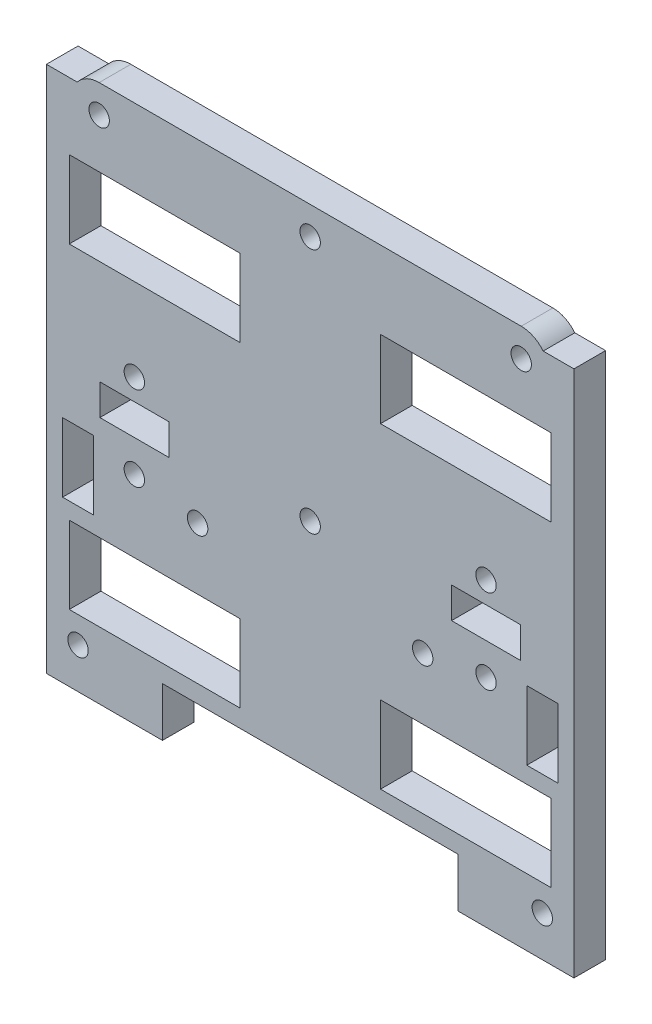
SolidWorks part; units mm, degrees
ref_plane "Front Plane" through (0, 0, 0) normal (0, 0, 1) x (1, 0, 0)
ref_plane "Top Plane" through (0, 0, 0) normal (0, 1, 0) x (1, 0, 0)
ref_plane "Right Plane" through (0, 0, 0) normal (1, 0, 0) x (0, 0, -1)
sketch "Sketch1" plane through (0, 0, 0) normal (0, 0, 1) x (1, 0, 0)
  line L0 (0, -37.5) -> (0, 37.5) construction
  line L1 (-47.5, -37.5) -> (47.5, -37.5)
  line L2 (-47.5, -37.5) -> (-47.5, 37.5)
  line L3 (-47.5, 37.5) -> (47.5, 37.5)
  line L4 (47.5, -37.5) -> (47.5, 37.5)
  line L5 (-47.5, -37.5) -> (47.5, 37.5) construction
  line L6 (-47.5, 37.5) -> (47.5, -37.5) construction
  line L7 (-47.5, 0) -> (47.5, 0) construction
  line L8 (-47.5, 22.5) -> (47.5, 22.5) construction
  line L9 (34.25, 17) -> (10, 28) construction
  line L10 (-34.25, 28) -> (-10, 28)
  line L11 (-34.25, 28) -> (-34.25, 17)
  line L12 (-34.25, 17) -> (-10, 17)
  line L13 (-10, 28) -> (-10, 17)
  line L14 (-34.25, 28) -> (-10, 17) construction
  line L15 (-34.25, 17) -> (-10, 28) construction
  line L16 (34.25, 28) -> (10, 17) construction
  line L17 (10, 28) -> (10, 17)
  line L18 (34.25, 17) -> (10, 17)
  line L19 (34.25, 28) -> (34.25, 17)
  line L20 (34.25, 28) -> (10, 28)
  line L21 (34.25, -28) -> (10, -17) construction
  line L22 (-34.25, -17) -> (-10, -28) construction
  line L23 (-34.25, -28) -> (-10, -17) construction
  line L24 (34.25, -17) -> (10, -28) construction
  line L25 (34.25, -28) -> (10, -28)
  line L26 (34.25, -28) -> (34.25, -17)
  line L27 (34.25, -17) -> (10, -17)
  line L28 (10, -28) -> (10, -17)
  line L29 (-10, -28) -> (-10, -17)
  line L30 (-34.25, -17) -> (-10, -17)
  line L31 (-34.25, -28) -> (-34.25, -17)
  line L32 (-34.25, -28) -> (-10, -28)
  point P0 (0, 0)
  point P12 (-22.125, 22.5)
  point P21 (22.125, 22.5)
  point P30 (22.125, -22.5)
  point P31 (-22.125, -22.5)
  dimension "D1" = 95
  dimension "D2" = 75
  dimension "D3" = 22.5
  dimension "D4" = 24.25
  dimension "D5" = 11
  dimension "D6" = 10
extrude "Boss-Extrude1" add sketch "Sketch1" along normal blind 4.5
sketch "Sketch8" plane through (0, 0, 4.5) normal (0, 0, 1) x (1, 0, 0)
  line L0 (-47.5, 37.5) -> (-47.5, -37.5) construction
  line L1 (47.5, -37.5) -> (47.5, 37.5) construction
  circle A0 centre (-47.5, 29.5) radius 8
  circle A1 centre (47.5, 29.5) radius 8
  dimension "D1" = 16
extrude "Boss-Extrude2" [suppressed] add sketch "Sketch8" against normal through all
sketch "Sketch2" plane through (0, 0, 4.5) normal (0, 0, 1) x (1, 0, 0)
  line L0 (0, -37.5) -> (0, 37.5) construction
  line L1 (-47.5, -37.5) -> (47.5, -37.5) construction
  line L2 (47.5, 37.5) -> (-47.5, 37.5) construction
  line L3 (-47.5, 0) -> (47.5, 0) construction
  line L4 (-47.5, 37.5) -> (-47.5, -37.5) construction
  line L5 (47.5, -37.5) -> (47.5, 37.5) construction
  line L6 (-40, 0) -> (40, 0) construction
  line L7 (-30, 35) -> (30, 35) construction
  circle A0 centre (-30, 35) radius 1.45
  circle A1 centre (30, 35) radius 1.45
  circle A2 centre (40, 0) radius 1.45
  circle A3 centre (-40, 0) radius 1.45
  circle A4 centre (0, 35) radius 1.45
  dimension "D1" = 2.9
  dimension "D7" = 2.9
  dimension "D8" = 2.9
  dimension "D9" = 2.9
  dimension "D2" = 30
  dimension "D3" = 35
  dimension "D4" = 80
  dimension "D5" = 40
  dimension "D6" = 0
extrude "screwHoles" cut sketch "Sketch2" against normal through all
sketch "Sketch3" plane through (0, 0, 4.5) normal (0, 0, 1) x (1, 0, 0)
  line L0 (-47.5, -20) -> (26.0486, -20) construction
  line L1 (-47.5, 37.5) -> (-47.5, -37.5) construction
  line L3 (0, 37.5) -> (0, -37.5) construction
  line L4 (47.5, 37.5) -> (-47.5, 37.5) construction
  line L5 (-47.5, -37.5) -> (47.5, -37.5) construction
  line L6 (18.95, -22.2) -> (9.05, -17.8) construction
  line L7 (-18.95, -17.8) -> (-9.05, -17.8)
  line L8 (-18.95, -17.8) -> (-18.95, -22.2)
  line L9 (-18.95, -22.2) -> (-9.05, -22.2)
  line L10 (-9.05, -17.8) -> (-9.05, -22.2)
  line L11 (-18.95, -17.8) -> (-9.05, -22.2) construction
  line L12 (-18.95, -22.2) -> (-9.05, -17.8) construction
  line L13 (18.95, -17.8) -> (9.05, -22.2) construction
  line L14 (9.05, -17.8) -> (9.05, -22.2)
  line L15 (18.95, -22.2) -> (9.05, -22.2)
  line L16 (18.95, -17.8) -> (18.95, -22.2)
  line L17 (18.95, -17.8) -> (9.05, -17.8)
  line L18 (-47.5, 37.5) -> (-47.5, -37.5) construction
  point P2 (-47.5, 0)
  point P12 (-14, -20)
  point P21 (14, -20)
  dimension "D1" = 9.9
  dimension "D2" = 4.4
  dimension "D3" = 14
  dimension "D4" = 20
extrude "BeltClamp" [suppressed] cut sketch "Sketch3" against normal through all
sketch "Sketch4" plane through (0, 0, 4.5) normal (0, 0, 1) x (1, 0, 0)
  line L0 (-47.5, 0) -> (47.5, 0) construction
  line L1 (-47.5, 37.5) -> (-47.5, -37.5) construction
  line L2 (47.5, -37.5) -> (47.5, 37.5) construction
  line L3 (0, 0) -> (0, 33.55) construction
  line L4 (-29.9, 2.2) -> (-20.1, 2.2)
  line L5 (-29.9, 2.2) -> (-29.9, -2.2)
  line L6 (-29.9, -2.2) -> (-20.1, -2.2)
  line L7 (-20.1, 2.2) -> (-20.1, -2.2)
  line L8 (-29.9, 2.2) -> (-20.1, -2.2) construction
  line L9 (-29.9, -2.2) -> (-20.1, 2.2) construction
  line L10 (29.9, -2.2) -> (20.1, 2.2) construction
  line L11 (29.9, 2.2) -> (20.1, -2.2) construction
  line L12 (20.1, 2.2) -> (20.1, -2.2)
  line L13 (29.9, -2.2) -> (20.1, -2.2)
  line L14 (29.9, 2.2) -> (29.9, -2.2)
  line L15 (29.9, 2.2) -> (20.1, 2.2)
  line L16 (-29.9, -2.2) -> (-20.1, 2.2) construction
  circle A0 centre (-40, 0) radius 1.45 construction
  circle A1 centre (0, 35) radius 1.45 construction
  circle A2 centre (0, 0) radius 1.45
  point P6 (-25, 0)
  point P22 (25, 0)
  dimension "D2" = 4.4
  dimension "D5" = 2.9
  dimension "D3" = 0
  dimension "D1" = 9.8
  dimension "D4" = 25
extrude "Cut-Extrude3" cut sketch "Sketch4" against normal through all
sketch "Sketch5" plane through (0, 0, 4.5) normal (0, 0, 1) x (1, 0, 0)
  line L0 (-47.5, -9.75) -> (47.5, -9.75) construction
  line L1 (-47.5, 37.5) -> (-47.5, -37.5) construction
  line L2 (47.5, -37.5) -> (47.5, 37.5) construction
  line L4 (0, -37.5) -> (0, 37.5) construction
  line L5 (-47.5, -37.5) -> (47.5, -37.5) construction
  line L6 (47.5, 37.5) -> (-47.5, 37.5) construction
  line L7 (-30.8, -14.65) -> (-35.2, -4.85) construction
  line L8 (30.8, -4.85) -> (35.2, -4.85)
  line L9 (30.8, -4.85) -> (30.8, -14.65)
  line L10 (30.8, -14.65) -> (35.2, -14.65)
  line L11 (35.2, -4.85) -> (35.2, -14.65)
  line L12 (30.8, -4.85) -> (35.2, -14.65) construction
  line L13 (30.8, -14.65) -> (35.2, -4.85) construction
  line L14 (-30.8, -4.85) -> (-35.2, -14.65) construction
  line L15 (-35.2, -4.85) -> (-35.2, -14.65)
  line L16 (-30.8, -14.65) -> (-35.2, -14.65)
  line L17 (-30.8, -4.85) -> (-30.8, -14.65)
  line L18 (-30.8, -4.85) -> (-35.2, -4.85)
  line L19 (33, -9.75) -> (33, -37.5) construction
  line L20 (-33, -9.75) -> (-33, -37.5) construction
  line L21 (-33, -31.75) -> (33, -31.75) construction
  circle A0 centre (33, -31.75) radius 1.45
  circle A1 centre (-33, -31.75) radius 1.45
  point P15 (33, -9.75)
  point P24 (-33, -9.75)
  dimension "D5" = 2.9
  dimension "D2" = 9.8
  dimension "D3" = 4.4
  dimension "D4" = 33
  dimension "D6" = 22
  dimension "D1" = 9.75
extrude "Cut-Extrude4" cut sketch "Sketch5" against normal through all
sketch "Sketch9" plane through (0, 0, 4.5) normal (0, 0, 1) x (1, 0, 0)
  line L0 (47.5, 37.5) -> (-47.5, 37.5) construction
  line L1 (0, 37.5) -> (0, -37.5) construction
  line L2 (-47.5, -37.5) -> (47.5, -37.5) construction
  line L3 (50.5, 35) -> (45.5, 35) construction
  line L4 (-50.5, 35) -> (-45.5, 35) construction
  circle A0 centre (-30, 35) radius 4
  circle A1 centre (-30, 35) radius 1.45
  circle A2 centre (-30, 35) radius 1.45 construction
  circle A3 centre (30, 35) radius 1.45
  circle A4 centre (30, 35) radius 4
  point P17 (0, -37.5)
  dimension "D1" = 8
extrude "Boss-Extrude3" add sketch "Sketch9" against normal through all
sketch "Sketch10" plane through (0, 0, 4.5) normal (0, 0, 1) x (1, 0, 0)
  line L0 (-60, 37.5) -> (-37.5, 37.5)
  line L1 (-37.5, 37.5) -> (-37.5, -37.5)
  line L2 (-47.5, -37.5) -> (47.5, -37.5) construction
  line L3 (-37.5, -37.5) -> (-60, -37.5)
  line L4 (-60, -37.5) -> (-60, 37.5)
  line L5 (0, 37.5) -> (0, -37.5) construction
  line L6 (26.8775, 37.5) -> (-26.8775, 37.5) construction
  line L7 (60, -37.5) -> (60, 37.5)
  line L8 (37.5, -37.5) -> (60, -37.5)
  line L9 (37.5, 37.5) -> (37.5, -37.5)
  line L10 (60, 37.5) -> (37.5, 37.5)
  line L11 (-60, -37.5) -> (-60, 37.5)
  line L12 (-33.1225, 37.5) -> (-47.5, 37.5) construction
  line M3 (47.5, -37.5) -> (47.5, 37.5)
  line M7 (-47.5, 37.5) -> (-47.5, -37.5)
  line M8 (-47.5, -37.5) -> (47.5, -37.5)
  dimension "D3" = 0
  dimension "D1" = 75
  dimension "D2" = 60
extrude "Cut-Extrude5" cut sketch "Sketch10" against normal through all contours L1 L0 M7 M8 | L10 L9 M3 M8
sketch "Sketch11" plane through (0, 0, 4.5) normal (0, 0, 1) x (1, 0, 0)
  line L0 (-30, 39) -> (30, 39)
  line L1 (30, 39) -> (26.8775, 37.5)
  line L2 (26.8775, 37.5) -> (-26.8775, 37.5)
  line L3 (-26.8775, 37.5) -> (-30, 39)
  arc A0 (-26.8775, 37.5) -> (-33.1225, 37.5) centre (-30, 35) ccw construction
  arc A1 (33.1225, 37.5) -> (26.8775, 37.5) centre (30, 35) ccw construction
extrude "Boss-Extrude4" add sketch "Sketch11" against normal through all
sketch "Sketch12" plane through (0, 0, 4.5) normal (0, 0, 1) x (1, 0, 0)
  line L0 (-37.5, -8.25) -> (37.5, -8.25) construction
  line L1 (-37.5, 37.5) -> (-37.5, -37.5) construction
  line L2 (37.5, 37.5) -> (37.5, -37.5) construction
  line L3 (0, 0) -> (0, -37.5) construction
  line L4 (-37.5, -37.5) -> (37.5, -37.5) construction
  circle A0 centre (-16, -8.25) radius 1.45
  circle A1 centre (16, -8.25) radius 1.45
  dimension "D2" = 2.9
  dimension "D1" = 16
  dimension "D3" = 8.25
extrude "FanBraceScrews" cut sketch "Sketch12" against normal through all
sketch "Sketch13" plane through (0, 0, 4.5) normal (0, 0, 1) x (1, 0, 0)
  line L0 (-37.5, -37.5) -> (37.5, -37.5) construction
  line L1 (-21, -44.5) -> (21, -44.5)
  line L2 (-21, -44.5) -> (-21, -30.5)
  line L3 (-21, -30.5) -> (21, -30.5)
  line L4 (21, -44.5) -> (21, -30.5)
  line L5 (-21, -44.5) -> (21, -30.5) construction
  line L6 (-21, -30.5) -> (21, -44.5) construction
  point P0 (0, -37.5)
  dimension "D1" = 42
  dimension "D2" = 7
extrude "Cut-Extrude7" cut sketch "Sketch13" against normal through all
sketch "Sketch14" plane through (0, 0, 4.5) normal (0, 0, 1) x (1, 0, 0)
  line L0 (16, -9.7) -> (16, 3.75) construction
  line L1 (0, 0) -> (0, -40.3958) construction
  line L2 (-16, -9.7) -> (-16, 3.75) construction
  circle A0 centre (16, -8.25) radius 1.45 construction
  circle A1 centre (16, 3.75) radius 1.45
  circle A2 centre (-16, 3.75) radius 1.45
  dimension "D2" = 2.9
  dimension "D1" = 12
extrude "Cut-Extrude8" [suppressed] cut sketch "Sketch14" against normal through all
sketch "Sketch15" plane through (0, 0, 4.5) normal (0, 0, 1) x (1, 0, 0)
  line L0 (-25, 5.25) -> (-25, -6.75) construction
  line L2 (0, 0) -> (0, -11.0705) construction
  line L3 (16, -8.3509) -> (25, -6.75) construction
  line L4 (25, 5.25) -> (25, -6.75) construction
  circle A0 centre (-25, 5.25) radius 1.45
  circle A1 centre (-25, -6.75) radius 1.45
  circle A2 centre (25, -6.75) radius 1.45
  circle A3 centre (25, 5.25) radius 1.45
  circle A5 centre (-16, -8.25) radius 1.45 construction
  dimension "D1" = 12
  dimension "D3" = 2.9
  dimension "D4" = 2.9
  dimension "D2" = 25
  dimension "D5" = 1.5
extrude "BeltClipScrews" cut sketch "Sketch15" against normal through all
sketch "Sketch16" [suppressed] plane through (0, 0, 4.5) normal (0, 0, 1) x (1, 0, 0)
  line L0 (0, 0) -> (0, -11.3016) construction
  line L1 (-30.1, 2.35) -> (-19.9, 2.35)
  line L2 (-30.1, 2.35) -> (-30.1, -2.35)
  line L3 (-30.1, -2.35) -> (-19.9, -2.35)
  line L4 (-19.9, 2.35) -> (-19.9, -2.35)
  line L5 (-35.35, -4.65) -> (-30.65, -4.65)
  line L6 (-35.35, -4.65) -> (-35.35, -14.85)
  line L7 (-35.35, -14.85) -> (-30.65, -14.85)
  line L8 (-30.65, -4.65) -> (-30.65, -14.85)
  line L9 (30.65, -4.65) -> (30.65, -14.85)
  line L10 (35.35, -14.85) -> (30.65, -14.85)
  line L11 (35.35, -4.65) -> (35.35, -14.85)
  line L12 (35.35, -4.65) -> (30.65, -4.65)
  line L13 (19.9, 2.35) -> (19.9, -2.35)
  line L14 (30.1, -2.35) -> (19.9, -2.35)
  line L15 (30.1, 2.35) -> (30.1, -2.35)
  line L16 (30.1, 2.35) -> (19.9, 2.35)
  line L17 (-30.65, -4.65) -> (-30.65, -14.85)
extrude "Boss-Extrude5" [suppressed] add sketch "Sketch16" against normal through all contours L8 L5 L6 L7 | L4 L1 L2 L3 | L15 L16 L13 L14 | L11 L12 L9 L10
equation "\"X-ROD-SPACING\"=45"
equation "\"Y-ROD-SPACING\"=75"
equation "\"Z-ROD-SPACING\"=17.5"
equation "\"Y-BED-OFFSET\"=2"
equation "\"Y-BED-ROD-INSET\"=3.5"
equation "\"Y-BED-SCREW-SPACING\"=209"
equation "\"Y-BED-SCREW-CUTOUT-SLOT-HEIGHT\"=2"
equation "\"T-SLOT-NUT-FILLET-RADIUS\"=0.5"
equation "\"T-SLOT-SCREW-SHAFT-RADIUS\"=1.55"
equation "\"T-SLOT-SCREW-SHAFT-CUTOUT-LENGTH\"=11.0"
equation "\"T-SLOT-NUT-DEPTH\"=3.5"
equation "\"T-SLOT-NUT-WIDTH\"=2.85"
equation "\"T-SLOT-NUT-END-DISTANCE\"=8"
equation "\"ACRYLIC-THICKNESS\"=10"
equation "\"ACRYLIC-THICKNESS2\"=4.5"
equation "\"ACRYLIC-TAB-CUTOUT-SIZE\"=\"ACRYLIC-THICKNESS\"+\"ACRYLIC-TAB-TOLERANCE\"*2"
equation "\"ACRYLIC-TAB-WIDTH\"=\"ACRYLIC-THICKNESS\""
equation "\"ACRYLIC-M3-HOLE\"=2.9"
equation "\"SMOOTHROD-CAP-SCREW-DISTANCE\"=20"
equation "\"FRAME-WIDTH-INNER\"=370"
equation "\"NEMA17-HOLE-SPACING\"=31"
equation "\"NEMA17-CENTRAL-CUTOUT\"=22.5"
equation "\"Z-BRACKET-REACH\"=55"
equation "\"Z-ROD-INSET\"=16"
equation "\"TOP-BRACKET-SPACING\"=40"
equation "\"SMOOTHROD-X-LENGTH\"=350"
equation "\"SMOOTHROD-Y-LENGTH\"=350"
equation "\"SMOOTHROD-Z-LENGTH\"=350"
equation "\"SMOOTHROD-TIGHTENING-HEADROOM\"=.25"
equation "\"LEADSCREW-Z-LENGTH\"=300"
equation "\"SCREW-LENGTH-FRAME\"=\"ACRYLIC-THICKNESS\" + 10"
equation "\"SCREW-LENGTH-MOTOR\"=\"ACRYLIC-THICKNESS\" + 5"
equation "\"SCREW-HEAD-RADIUS\"=6"
equation "\"PRINTED-X-SMOOTHROD-DIAMETER\"=9.4"
equation "\"PRINTED-X-SMOOTHROD-CUTOUT\"=10"
equation "\"PRINTED-X-BASE-HEIGHT\"=10"
equation "\"PRINTED-LM8UU-CUTOUT-SIZE\"=15.5"
equation "\"PRINTED-LM8UU-CUTOUT-LENGTH\"=24.5"
equation "\"PRINTED-X-IDLER-HEIGHT\"=16"
equation "\"PSU-MOUNTING-WIDTH\"=95"
equation "\"PSU-MOUNTING-HEIGHT\"=177"
equation "\"Y-BELT-TO-ROD-DISTANCE\"=20"
equation "\"SPOOL-HOLDER-ROD-SPACING\"=150"
equation "\"D3@Sketch1\"=\"X-ROD-SPACING\"/2"
equation "\"D4@Sketch1\"=\"ACRYLIC-X-CARRIAGE-LM8UU-CUTOUT-WIDTH\""
equation "\"D1@Boss-Extrude1\"=\"ACRYLIC-THICKNESS2\""
equation "\"D1@Sketch2\"=\"ACRYLIC-M3-HOLE\""
equation "\"D1@Sketch3\"=\"ACRYLIC-TAB-CUTOUT-SIZE\""
equation "\"D2@Sketch3\"=\"ACRYLIC-THICKNESS2\"+\"ACRYLIC-TAB-TOLERANCE\"*2"
equation "\"ACRYLIC-X-CARRIAGE-WIDTH\"=55"
equation "\"ACRYLIC-X-CARRIAGE-HEIGHT\"=75"
equation "\"D2@Sketch1\"=\"ACRYLIC-X-CARRIAGE-HEIGHT\""
equation "\"ACRYLIC-X-CARRIAGE-CENTER-TAB-SPACING\"=14"
equation "\"D3@Sketch3\"=\"ACRYLIC-X-CARRIAGE-CENTER-TAB-SPACING\""
equation "\"SCREW-LENGTH-EXTRUDER\"=28"
equation "\"ACRYLIC-X-CARRIAGE-SCREW-SPACING-X\"=15"
equation "\"ACRYLIC-X-CARRIAGE-SCREW-SPACING-Y\"=33"
equation "\"D1@Sketch4\"=\"ACRYLIC-TAB-WIDTH\"-\"KERF\"*4"
equation "\"D2@Sketch4\"=\"ACRYLIC-THICKNESS2\"-\"KERF\"*2"
equation "\"D2@Sketch5\"=\"ACRYLIC-TAB-WIDTH\"-\"KERF\"*4"
equation "\"D3@Sketch5\"=\"ACRYLIC-THICKNESS2\"-\"KERF\"*2"
equation "\"ACRYLIC-X-CARRIAGE-EXTRUDER-SHELF-DEPTH\"=\"ACRYLIC-X-CARRIAGE-EXTRUDER-OFFSET\" + 28"
equation "\"ACRYLIC-X-CARRIAGE-EXTRUDER-BRACE-SPACING\"=23"
equation "\"D4@Sketch5\"=\"ACRYLIC-X-CARRIAGE-DUAL-MOUNT-BRACE-WIDTH\""
equation "\"D1@Sketch5\"=\"ACRYLIC-THICKNESS2\"/2 + 7.5"
equation "\"D4@Sketch2\"=\"ACRYLIC-X-CARRIAGE-DUAL-MOUNT-SCREW-WIDTH\"*2"
equation "\"D5@Sketch2\"=\"ACRYLIC-X-CARRIAGE-DUAL-MOUNT-SCREW-WIDTH\""
equation "\"D7@Sketch2\"=\"ACRYLIC-M3-HOLE\""
equation "\"D8@Sketch2\"=\"ACRYLIC-M3-HOLE\""
equation "\"ACRYLIC-X-CARRIAGE-LM8UU-CUTOUT-WIDTH\"=24.25"
equation "\"ACRYLIC-TAB-TOLERANCE\"=-.05"
equation "\"ACRYLIC-X-CARRIAGE-EXTRUDER-OFFSET\"=26"
equation "\"ACRYLIC-X-CARRIAGE-EXTRUDER-ANGLE\"=90"
equation "\"ACRYLIC-X-CARRIAGE-EXTRUDER-BRACE-TAB-OFFSET\"=20"
equation "\"ACRYLIC-X-CARRIAGE-EXTRUDER-BRACE-HEIGHT\"=35"
equation "\"ACRYLIC-X-CARRIAGE-EXTRUDER-BRACE-SCREW-SPACING\"=22"
equation "\"D5@Sketch5\"=\"ACRYLIC-M3-HOLE\""
equation "\"ACRYLIC-X-CARRIAGE-DUAL-WIDTH-MULTIPLIER\"=1.65"
equation "\"ACRYLIC-X-CARRIAGE-DUAL-HOTEND-SPACING\"=42"
equation "\"ACRYLIC-X-CARRIAGE-DUAL-WIDTH\"=75"
equation "\"ACRYLIC-X-CARRIAGE-DUAL-HOTEND-SEPARATION\"=36"
equation "\"ACRYLIC-X-CARRIAGE-DUAL-MOUNT-PLATE-DEPTH\"=75"
equation "\"ACRYLIC-X-CARRIAGE-DUAL-MOUNT-BRACE-WIDTH\"=33"
equation "\"ACRYLIC-X-CARRIAGE-DUAL-MOUNT-SCREW-WIDTH\"=40"
equation "\"D9@Sketch2\"=\"ACRYLIC-M3-HOLE\""
equation "\"ACRYLIC-X-CARRIAGE-LM8UU-CUTOUT-HEIGHT\"=11.0"
equation "\"D5@Sketch1\"=\"ACRYLIC-X-CARRIAGE-LM8UU-CUTOUT-HEIGHT\""
equation "\"D1@Sketch10\"=\"ACRYLIC-X-CARRIAGE-DUAL-WIDTH\""
equation "\"D5@Sketch4\"=\"ACRYLIC-M3-HOLE\""
equation "\"D2@Sketch12\"=\"ACRYLIC-M3-HOLE\""
equation "\"D3@Sketch12\"=\"ACRYLIC-THICKNESS2\"/2 + 6"
equation "\"D2@Sketch14\"=\"ACRYLIC-M3-HOLE\""
equation "\"D3@Sketch15\"=\"ACRYLIC-M3-HOLE\""
equation "\"D4@Sketch15\"=\"ACRYLIC-M3-HOLE\""
equation "\"KERF\"=0.05"
equation "\"ACRYLIC-THICKNESS-TAB-CUTOUT-WIDTH\"=\"ACRYLIC-THICKNESS\"-\"KERF\"*2"
equation "\"ACRYLIC-THICKNESS-TAB-CUTOUT-HEIGHT\"=\"ACRYLIC-TAB-WIDTH\"-\"KERF\"*4"
equation "\"ACRYLIC-THICKNESS2-TAB-CUTOUT-WIDTH\"=\"ACRYLIC-THICKNESS2\"-\"KERF\"*2"
equation "\"ACRYLIC-THICKNESS2-TAB-CUTOUT-HEIGHT\"=\"ACRYLIC-TAB-WIDTH\"-\"KERF\"*4"
equation "\"PRINTED-M3-HOLE\"=3.5"
equation "\"PRINTED-M3-NUT-AF\"=6.25"
equation "\"ACRYLIC-X-CARRIAGE-DUAL-FAN-OFFSET\"=52"
equation "\"ACRYLIC-X-CARRIAGE-DUAL-FAN-HEIGHT\"=20"
equation "\"BLOWER-FAN-WIDTH\"=15"
